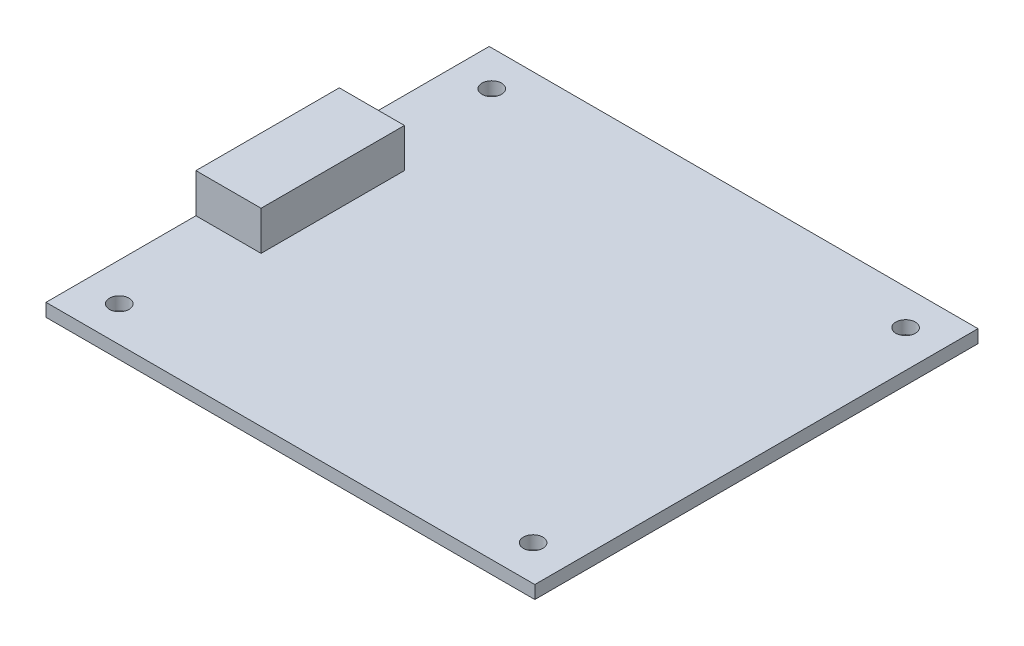
SolidWorks part; units mm, degrees
ref_plane "Front Plane" through (0, 0, 0) normal (0, 0, 1) x (1, 0, 0)
ref_plane "Top Plane" through (0, 0, 0) normal (0, 1, 0) x (1, 0, 0)
ref_plane "Right Plane" through (0, 0, 0) normal (1, 0, 0) x (0, 0, -1)
sketch "Sketch1" plane through (0, 0, 0) normal (0, 1, 0) x (1, 0, 0)
  line L1 (-37.5, -34) -> (37.5, -34)
  line L2 (-37.5, -34) -> (-37.5, 34)
  line L3 (-37.5, 34) -> (37.5, 34)
  line L4 (37.5, -34) -> (37.5, 34)
  line L5 (-37.5, -34) -> (37.5, 34) construction
  line L6 (-37.5, 34) -> (37.5, -34) construction
  circle A0 centre (31.8135, 28.575) radius 1.5
  circle A1 centre (31.8135, -28.575) radius 1.5
  circle A2 centre (-31.6865, 28.575) radius 1.5
  circle A3 centre (-31.6865, -28.575) radius 1.5
  point P0 (0, 0)
  point P20 (0, 0)
  dimension "D3" = 3
  dimension "D4" = 3
  dimension "D5" = 3
  dimension "D6" = 3
  dimension "D1" = 75
  dimension "D2" = 68
extrude "Boss-Extrude1" add sketch "Sketch1" along normal blind 2
sketch "Sketch2" plane through (0, 0, 0) normal (0, -1, 0) x (1, 0, 0)
  circle A0 centre (-21.5929, 0) radius 3
  dimension "D1" = 6
extrude "Boss-Extrude2" add sketch "Sketch2" along normal blind 10
sketch "Sketch3" plane through (0, 0, 0) normal (0, -1, 0) x (1, 0, 0)
  circle A0 centre (-21.7439, -7.9275) radius 2
  dimension "D1" = 4
extrude "Boss-Extrude3" add sketch "Sketch3" along normal blind 8
fillet "Fillet1" radius 0.3 2 edges at (-21.7439, -8, -9.9275) (-21.5929, -10, -3)
sketch "Sketch4" plane through (0, 2, 0) normal (0, 1, 0) x (1, 0, 0)
  line L0 (-37.5, 34) -> (-37.5, -34) construction
  line L1 (-37.5, -11) -> (-27.5, -11)
  line L2 (-37.5, -11) -> (-37.5, 11)
  line L3 (-37.5, 11) -> (-27.5, 11)
  line L4 (-27.5, -11) -> (-27.5, 11)
  line L5 (-37.5, -11) -> (-27.5, 11) construction
  line L6 (-37.5, 11) -> (-27.5, -11) construction
  point P0 (-32.5, 0)
  point P5 (-37.5, 0)
  dimension "D1" = 10
  dimension "D2" = 22
extrude "Boss-Extrude4" add sketch "Sketch4" along normal blind 6
